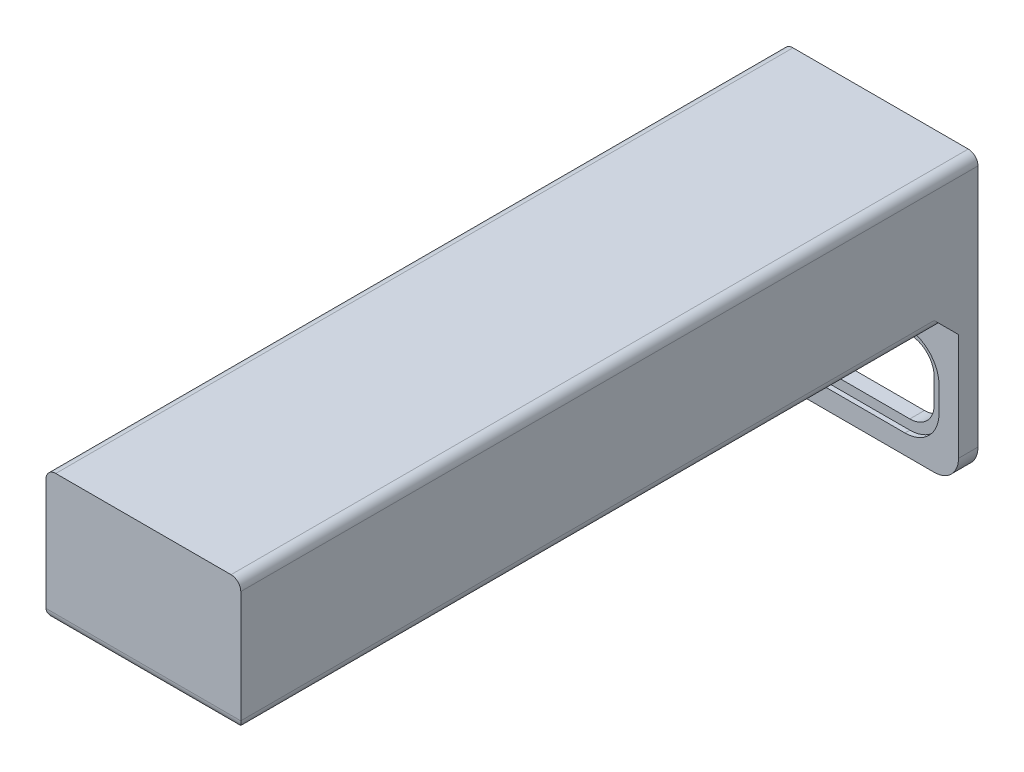
SolidWorks part; units mm, degrees
ref_plane "Plan de face" through (0, 0, 0) normal (0, 0, 1) x (1, 0, 0)
ref_plane "Plan de dessus" through (0, 0, 0) normal (0, 1, 0) x (1, 0, 0)
ref_plane "Plan de droite" through (0, 0, 0) normal (1, 0, 0) x (0, 0, -1)
sketch "Esquisse1" plane through (0, 0, 0) normal (0, 0, 1) x (1, 0, 0)
  line L1 (-100, 67.5) -> (100, 67.5)
  line L2 (-100, 67.5) -> (-100, -67.5)
  line L3 (-100, -67.5) -> (100, -67.5)
  line L4 (100, 67.5) -> (100, -67.5)
  line L5 (-100, 67.5) -> (100, -67.5) construction
  line L6 (-100, -67.5) -> (100, 67.5) construction
  point P0 (0, 0)
  dimension "D1" = 135
  dimension "D2" = 200
extrude "Boss.-Extru.1" add sketch "Esquisse1" along normal blind 727
shell "Coque1" thickness 10
sketch "Esquisse2" plane through (0, -67.5, 0) normal (0, -1, 0) x (1, 0, 0)
  line L0 (-70, 707) -> (-70, 207)
  line L2 (-70, 207) -> (-50, 207)
  line L3 (-50, 207) -> (-50, 707)
  line L4 (-50, 707) -> (-70, 707)
  line L5 (-100, 727) -> (100, 727) construction
  line L6 (0, 707) -> (0, 0) construction
  line L7 (-100, 0) -> (100, 0) construction
  line L8 (-100, 727) -> (-100, 0) construction
  line L9 (50, 207) -> (50, 707)
  line L10 (70, 207) -> (50, 207)
  line L11 (70, 707) -> (70, 207)
  line L12 (50, 707) -> (70, 707)
  point P10 (0, 707)
  dimension "D1" = 500
  dimension "D2" = 20
  dimension "D3" = 20
  dimension "D4" = 30
extrude "Enlèv. mat.-Extru.1" cut sketch "Esquisse2" against normal blind 10
sketch "Esquisse3" plane through (0, 0, 0) normal (0, 0, -1) x (-1, 0, 0)
  line L0 (-100, -67.5) -> (-100, 67.5) construction
  line L1 (-100, -217.5) -> (100, -217.5)
  line L2 (-100, -217.5) -> (-100, -67.5)
  line L3 (-100, -67.5) -> (100, -67.5)
  line L4 (100, -217.5) -> (100, -67.5)
  line L5 (-100, -217.5) -> (100, -67.5) construction
  line L6 (-100, -67.5) -> (100, -217.5) construction
  point P0 (0, -142.5)
  dimension "D1" = 150
extrude "Boss.-Extru.2" add sketch "Esquisse3" against normal blind 20
chamfer "Chanfrein1" distance 15 angle 45 1 edges at (0, -67.5, 20)
sketch "Esquisse4" plane through (0, 0, 20) normal (0, 0, 1) x (1, 0, 0)
  line L0 (70, -187.5) -> (70, -112.5)
  line L1 (70, -112.5) -> (-70, -112.5)
  line L2 (-70, -112.5) -> (-70, -187.5)
  line L3 (-70, -187.5) -> (70, -187.5)
  line L4 (100, -217.5) -> (100, -82.5)
  line L5 (100, -82.5) -> (-100, -82.5)
  line L6 (-100, -82.5) -> (-100, -217.5)
  line L7 (-100, -217.5) -> (100, -217.5)
  line L8 (100, -217.5) -> (100, -82.5)
  line L9 (100, -82.5) -> (-100, -82.5)
  line L10 (-100, -82.5) -> (-100, -217.5)
  line L11 (-100, -217.5) -> (100, -217.5)
  dimension "D1" = 0
  dimension "D2" = 30
extrude "Enlèv. mat.-Extru.2" cut sketch "Esquisse4" against normal through all contours L0 L1 L2 L3
fillet "Congé3" radius 25 4 edges at (-70, -187.5, 10) (70, -187.5, 10) (70, -112.5, 10) (-70, -112.5, 10)
fillet "Congé2" radius 25 2 edges at (100, -217.5, 10) (-100, -217.5, 10)
sketch "Esquisse5" plane through (0, 0, 20) normal (0, 0, 1) x (1, 0, 0)
  line L0 (70, -162.5) -> (70, -137.5) construction
  line L1 (-45, -187.5) -> (45, -187.5) construction
  line L2 (-70, -137.5) -> (-70, -162.5) construction
  line L3 (45, -112.5) -> (-45, -112.5) construction
  line L4 (70, -162.5) -> (70, -137.5)
  line L5 (-45, -187.5) -> (45, -187.5)
  line L6 (-70, -137.5) -> (-70, -162.5)
  line L7 (45, -112.5) -> (-45, -112.5)
  line L8 (45, -102.5) -> (-45, -102.5)
  line L9 (-80, -137.5) -> (-80, -162.5)
  line L10 (-45, -197.5) -> (45, -197.5)
  line L11 (80, -162.5) -> (80, -137.5)
  arc A0 (70, -137.5) -> (45, -112.5) centre (45, -137.5) ccw construction
  arc A1 (45, -187.5) -> (70, -162.5) centre (45, -162.5) ccw construction
  arc A2 (-70, -162.5) -> (-45, -187.5) centre (-45, -162.5) ccw construction
  arc A3 (-45, -112.5) -> (-70, -137.5) centre (-45, -137.5) ccw construction
  arc A4 (70, -137.5) -> (45, -112.5) centre (45, -137.5) ccw
  arc A5 (45, -187.5) -> (70, -162.5) centre (45, -162.5) ccw
  arc A6 (-70, -162.5) -> (-45, -187.5) centre (-45, -162.5) ccw
  arc A7 (-45, -112.5) -> (-70, -137.5) centre (-45, -137.5) ccw
  arc A8 (80, -137.5) -> (45, -102.5) centre (45, -137.5) ccw
  arc A9 (-45, -102.5) -> (-80, -137.5) centre (-45, -137.5) ccw
  arc A10 (-80, -162.5) -> (-45, -197.5) centre (-45, -162.5) ccw
  arc A11 (45, -197.5) -> (80, -162.5) centre (45, -162.5) ccw
  dimension "D1" = 10
extrude "Enlèv. mat.-Extru.3" cut sketch "Esquisse5" against normal blind 5
sketch "Esquisse6" plane through (0, 0, 15) normal (0, 0, 1) x (1, 0, 0)
  line L0 (0, -102.5) -> (0, -112.5) construction
  line L3 (-45, -187.5) -> (45, -187.5) construction
  line L4 (45, -102.5) -> (-45, -102.5)
  line L5 (-80, -137.5) -> (-80, -162.5)
  line L6 (-45, -197.5) -> (45, -197.5)
  line L7 (80, -162.5) -> (80, -137.5)
  line L8 (45, -102.5) -> (-45, -102.5)
  line L9 (-80, -137.5) -> (-80, -162.5)
  line L10 (-45, -197.5) -> (45, -197.5)
  line L11 (80, -162.5) -> (80, -137.5)
  line L13 (0, -187.5) -> (0, -197.5) construction
  circle A0 centre (-75, -150) radius 1.5
  circle A1 centre (75, -150) radius 1.5
  circle A2 centre (0, -107.5) radius 1.5
  circle A3 centre (0, -192.5) radius 1.5
  arc A4 (80, -137.5) -> (45, -102.5) centre (45, -137.5) ccw
  arc A5 (-45, -102.5) -> (-80, -137.5) centre (-45, -137.5) ccw
  arc A6 (-80, -162.5) -> (-45, -197.5) centre (-45, -162.5) ccw
  arc A7 (45, -197.5) -> (80, -162.5) centre (45, -162.5) ccw
  arc A8 (80, -137.5) -> (45, -102.5) centre (45, -137.5) ccw
  arc A9 (-45, -102.5) -> (-80, -137.5) centre (-45, -137.5) ccw
  arc A10 (-80, -162.5) -> (-45, -197.5) centre (-45, -162.5) ccw
  arc A11 (45, -197.5) -> (80, -162.5) centre (45, -162.5) ccw
  dimension "D4" = 3
  dimension "D5" = 3
  dimension "D2" = 5
  dimension "D3" = 12.5
  dimension "D1" = 0
sketch "Esquisse8" plane through (0, 0, 727) normal (0, 0, 1) x (1, 0, 0)
  line L4 (100, -67.5) -> (100, 67.5)
  line L5 (100, 67.5) -> (-100, 67.5)
  line L6 (-100, 67.5) -> (-100, -67.5)
  line L7 (-100, -67.5) -> (100, -67.5)
  line L8 (100, -67.5) -> (100, 67.5)
  line L9 (100, 67.5) -> (-100, 67.5)
  line L10 (-100, 67.5) -> (-100, -67.5)
  line L11 (-100, -67.5) -> (100, -67.5)
  dimension "D1" = 0
extrude "Boss.-Extru.3" add sketch "Esquisse8" along normal blind 30
fillet "Congé5" radius 10 5 edges at (100, 67.5, 378.5) (-100, 67.5, 378.5) (100, -67.5, 396) (-100, -67.5, 396) (0, -67.5, 757)
